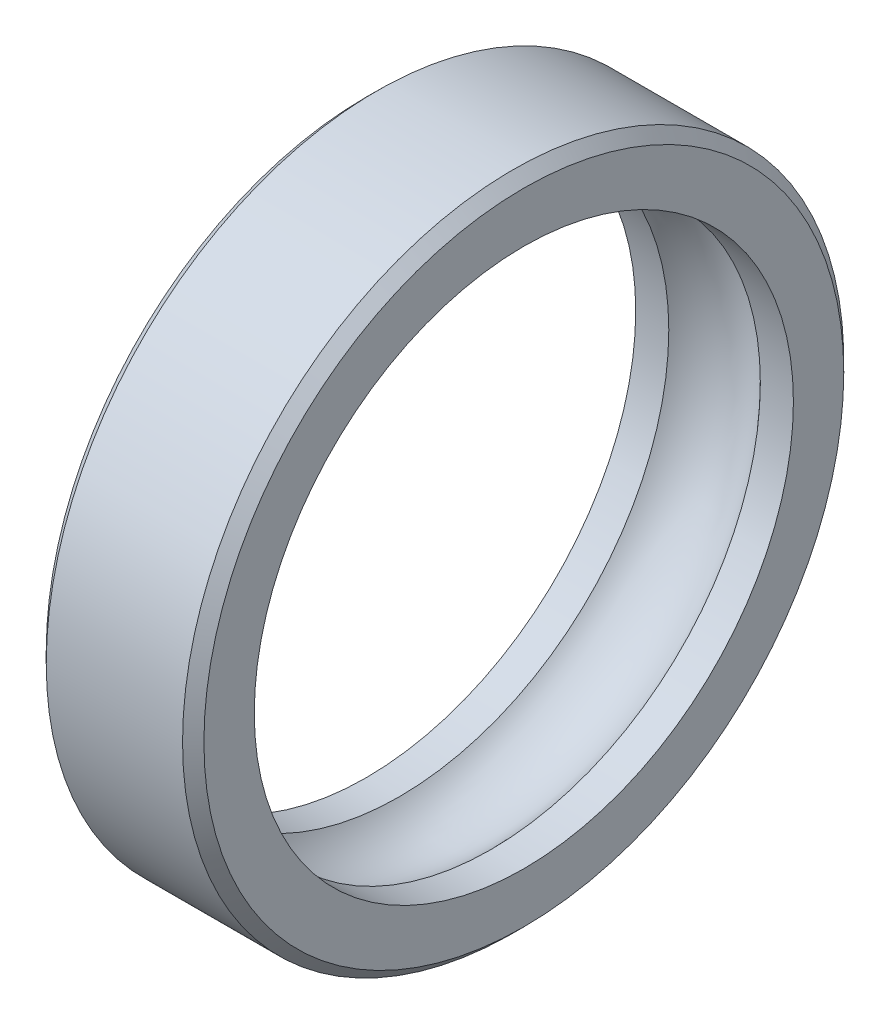
SolidWorks part; units mm, degrees
ref_plane "Front Plane" through (0, 0, 0) normal (0, 0, 1) x (1, 0, 0)
ref_plane "Top Plane" through (0, 0, 0) normal (0, 1, 0) x (1, 0, 0)
ref_plane "Right Plane" through (0, 0, 0) normal (1, 0, 0) x (0, 0, -1)
sketch "Sketch1" plane through (0, 0, 0) normal (0, 0, 1) x (1, 0, 0)
  line L0 (-8.5194, 0) -> (41.5415, 0) construction
  line L1 (0.388, 53.0627) -> (0, 0) construction
  line L2 (-15.1705, 65) -> (15.8295, 65)
  line L3 (-15.1705, 65) -> (-15.1705, 53)
  line L4 (-15.1705, 53) -> (-8.6705, 53)
  line L5 (15.8295, 65) -> (15.8295, 53)
  line L6 (9.3295, 53) -> (15.8295, 53)
  arc A0 (-8.6705, 53) -> (9.3295, 53) centre (0.3295, 45.0627) cw
  dimension "D5" = 12
  dimension "D1" = 31
  dimension "D2" = 65
  dimension "D3" = 6.5
  dimension "D4" = 6.5
revolve "Revolve1" add sketch "Sketch1" angle 360 about L0
chamfer "Chamfer1" distance 2.1 angle 45 2 edges at (15.8295, 0, 65) (-15.1705, 0, 65)
